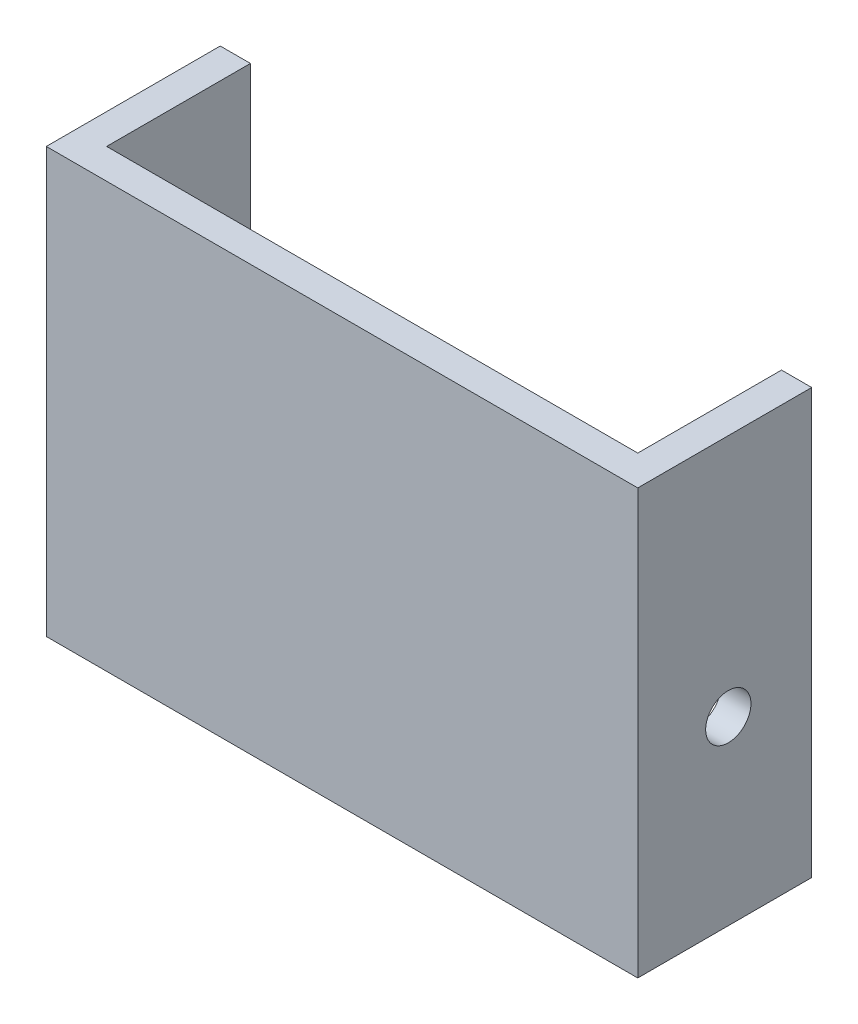
SolidWorks part; units mm, degrees
ref_plane "Front Plane" through (0, 0, 0) normal (0, 0, 1) x (1, 0, 0)
ref_plane "Top Plane" through (0, 0, 0) normal (0, 1, 0) x (1, 0, 0)
ref_plane "Right Plane" through (0, 0, 0) normal (1, 0, 0) x (0, 0, -1)
sketch "Sketch1" plane through (0, 0, 0) normal (0, 0, 1) x (1, 0, 0)
  line L1 (-17.6, -14.065) -> (17.6, -14.065)
  line L2 (-17.6, -14.065) -> (-17.6, 14.065)
  line L3 (-17.6, 14.065) -> (17.6, 14.065)
  line L4 (17.6, -14.065) -> (17.6, 14.065)
  line L5 (-17.6, -14.065) -> (17.6, 14.065) construction
  line L6 (-17.6, 14.065) -> (17.6, -14.065) construction
  point P0 (0, 0)
  dimension "D1" = 35.2
  dimension "D2" = 28.13
extrude "Boss-Extrude1" add sketch "Sketch1" along normal blind 2
sketch "Sketch2" plane through (17.6, 0, 0) normal (1, 0, 0) x (0, 0, -1)
  line L0 (-2, -14.065) -> (-2, 14.065) construction
  line L1 (-2, 14.065) -> (9.5282, 14.065)
  line L2 (-2, 14.065) -> (-2, -14.065)
  line L3 (-2, -14.065) -> (9.5282, -14.065)
  line L4 (9.5282, 14.065) -> (9.5282, -14.065)
  line L5 (-2, 14.065) -> (0, 14.065) construction
  line L6 (-2, -14.065) -> (0, -14.065) construction
extrude "Boss-Extrude2" add sketch "Sketch2" along normal blind 2
sketch "Sketch3" plane through (-17.6, 0, 0) normal (-1, 0, 0) x (0, 0, 1)
  line L0 (2, 14.065) -> (0, 14.065) construction
  line L1 (2, -14.065) -> (-9.5282, -14.065)
  line L2 (2, -14.065) -> (2, 14.065)
  line L3 (2, 14.065) -> (-9.5282, 14.065)
  line L4 (-9.5282, -14.065) -> (-9.5282, 14.065)
  line L7 (2, -14.065) -> (-9.5282, -14.065) construction
extrude "Boss-Extrude3" add sketch "Sketch3" along normal blind 2
sketch "Sketch4" plane through (19.6, 0, 0) normal (1, 0, 0) x (0, 0, -1)
  line L0 (-2, -14.065) -> (9.5282, -14.065) construction
  line L2 (0, 14.065) -> (0, -14.065) construction
  circle A0 centre (4, -2.065) radius 1.5
  dimension "D1" = 3
  dimension "D2" = 12
  dimension "D3" = 4
extrude "Cut-Extrude1" cut sketch "Sketch4" against normal through all
